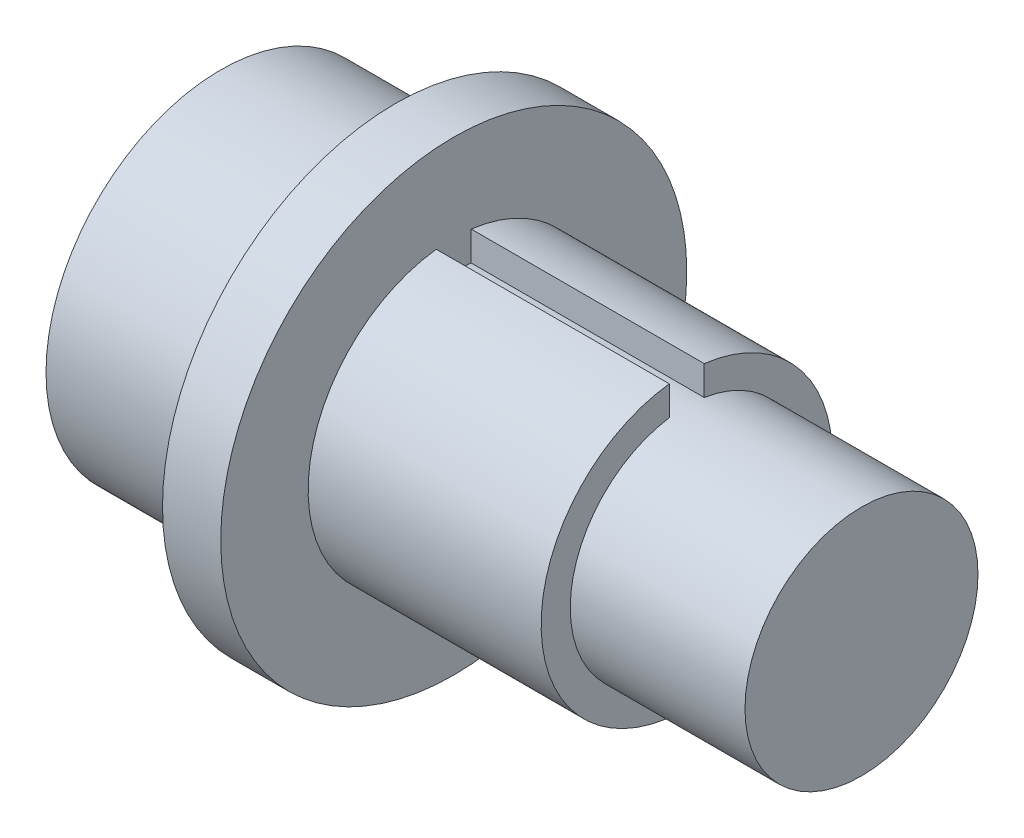
SolidWorks part; units mm, degrees
ref_plane "Front Plane" through (0, 0, 0) normal (0, 0, 1) x (1, 0, 0)
ref_plane "Top Plane" through (0, 0, 0) normal (0, 1, 0) x (1, 0, 0)
ref_plane "Right Plane" through (0, 0, 0) normal (1, 0, 0) x (0, 0, -1)
sketch "Sketch1" plane through (0, 0, 0) normal (0, 0, 1) x (1, 0, 0)
  line L0 (30, 30) -> (30, 40)
  line L1 (0, 0) -> (51.7159, 0)
  line L2 (0, 0) -> (0, 30)
  line L3 (0, 30) -> (30, 30)
  line L4 (30, 40) -> (40, 40)
  line L5 (40, 40) -> (40, 25)
  line L6 (40, 25) -> (80, 25)
  line L7 (110, 20) -> (110, 0)
  line L8 (110, 0) -> (51.7159, 0)
  line L9 (-14.6848, 0) -> (153.5516, 0) construction
  line L10 (80, 25) -> (80, 20)
  line L11 (80, 20) -> (110, 20)
  dimension "D1" = 30
  dimension "D2" = 10
  dimension "D3" = 10
  dimension "D4" = 30
  dimension "D5" = 70
  dimension "D6" = 40
  dimension "D7" = 25
  dimension "D8" = 5
revolve "Revolve2" add sketch "Sketch1" angle 360 about L9
sketch "Sketch2" plane through (80, 0, 0) normal (1, 0, 0) x (0, 0, -1)
  line L0 (-3, 24.8193) -> (-3, 19.7737)
  line L2 (3, 19.7737) -> (3, 24.8193)
  circle A0 centre (0, 0) radius 25 construction
  circle A1 centre (0, 0) radius 20 construction
  arc A2 (3, 24.8193) -> (-3, 24.8193) centre (0, 0) ccw
  arc A3 (3, 19.7737) -> (-3, 19.7737) centre (0, 0) ccw
  dimension "D1" = 6
  dimension "D2" = 3
extrude "Cut-Extrude1" cut sketch "Sketch2" against normal up to surface (40 mm away) up to face at (40, 0, 40)
